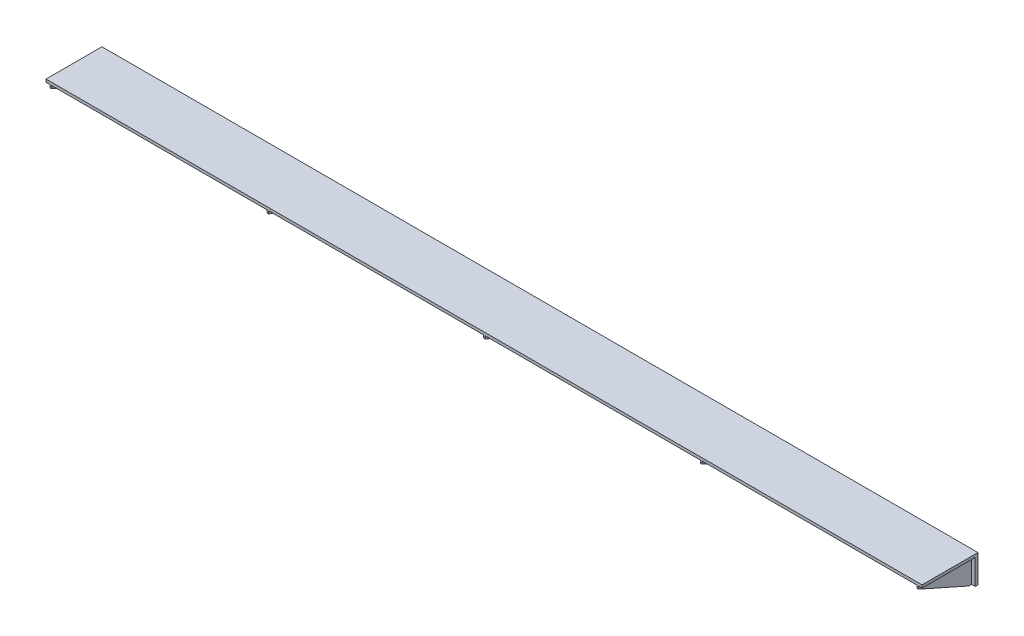
SolidWorks part; units mm, degrees
ref_plane "前视基准面" through (0, 0, 0) normal (0, 0, 1) x (1, 0, 0)
ref_plane "上视基准面" through (0, 0, 0) normal (0, 1, 0) x (1, 0, 0)
ref_plane "右视基准面" through (0, 0, 0) normal (1, 0, 0) x (0, 0, -1)
sketch "草图1" plane through (0, 0, 0) normal (0, 0, 1) x (1, 0, 0)
  line L1 (-3132.8, -100) -> (3132.8, -100)
  line L2 (-3132.8, -100) -> (-3132.8, 100)
  line L3 (-3132.8, 100) -> (3132.8, 100)
  line L4 (3132.8, -100) -> (3132.8, 100)
  line L5 (-3132.8, -100) -> (3132.8, 100) construction
  line L6 (-3132.8, 100) -> (3132.8, -100) construction
  point P0 (0, 0)
  dimension "D1" = 6265.6
  dimension "D2" = 200
extrude "凸台-拉伸1" add sketch "草图1" along normal blind 20
sketch "草图2" plane through (0, 0, 20) normal (0, 0, 1) x (1, 0, 0)
  line L0 (3132.8, -100) -> (3132.8, 100) construction
  line L1 (-3132.8, 100) -> (3132.8, 100)
  line L2 (-3132.8, 100) -> (-3132.8, 80)
  line L3 (-3132.8, 80) -> (3132.8, 80)
  line L4 (3132.8, 100) -> (3132.8, 80)
  dimension "D1" = 20
extrude "凸台-拉伸2" add sketch "草图2" along normal blind 380 separate body
sketch "草图3" plane through (-3132.8, 0, 0) normal (-1, 0, 0) x (0, 0, 1)
  line L0 (400, 80) -> (20, 80)
  line L1 (20, 80) -> (20, -100)
  line L2 (20, -100) -> (40, -100)
  line L3 (40, -100) -> (400, 60)
  line L4 (400, 60) -> (400, 80)
  dimension "D1" = 20
  dimension "D2" = 20
extrude "凸台-拉伸3" add sketch "草图3" against normal blind 10 from offset 30 offset against normal yes
pattern_linear "阵列(线性)1" count 5 spacing 1550 along (1, 0, 0) of "凸台-拉伸3"
sketch "草图4" plane through (0, 100, 0) normal (0, 1, 0) x (1, 0, 0)
  line L0 (-3132.8, -400) -> (-3132.8, 0) construction
  line L1 (3132.8, -400) -> (-3132.8, -400)
  line L2 (3132.8, -400) -> (3132.8, -300)
  line L3 (3132.8, -300) -> (-3132.8, -300)
  line L4 (-3132.8, -400) -> (-3132.8, -300)
  dimension "D1" = 100
extrude "凸台-拉伸4" [suppressed] add sketch "草图4" along normal blind 20 separate body
